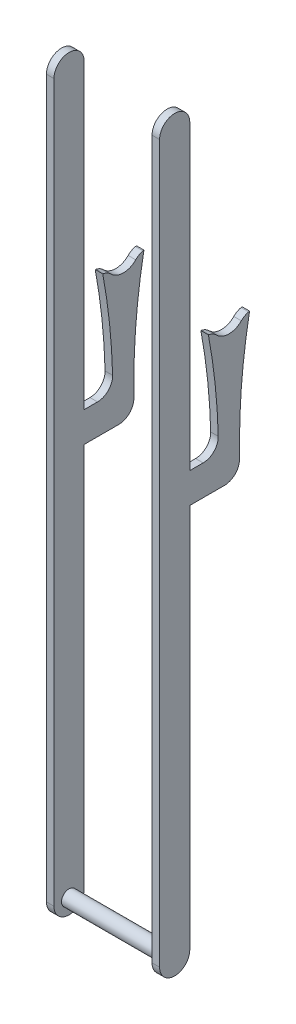
SolidWorks part; units mm, degrees
ref_plane "前视基准面" through (0, 0, 0) normal (0, 0, 1) x (1, 0, 0)
ref_plane "上视基准面" through (0, 0, 0) normal (0, 1, 0) x (1, 0, 0)
ref_plane "右视基准面" through (0, 0, 0) normal (1, 0, 0) x (0, 0, -1)
sketch "草图1" plane through (0, 0, 0) normal (0, 1, 0) x (1, 0, 0)
  line L0 (0, 0) -> (25601.3768, 0) construction
  line L1 (0, 0) -> (0, -25601.3768) construction
  line L2 (-65, -20) -> (-75, -20)
  line L3 (65, 20) -> (75, 20)
  line L4 (65, 20) -> (65, -20)
  line L5 (65, -20) -> (75, -20)
  line L6 (75, 20) -> (75, -20)
  line L7 (65, 20) -> (75, -20) construction
  line L8 (65, -20) -> (75, 20) construction
  line L9 (-75, 20) -> (-75, -20)
  line L10 (-65, 20) -> (-75, 20)
  line L11 (-65, 20) -> (-65, -20)
  point P5 (70, 0)
  dimension "D1" = 10
  dimension "D2" = 40
  dimension "D3" = 130
extrude "凸台-拉伸1" add sketch "草图1" along normal blind 950
sketch "草图2" plane through (75, 0, 0) normal (1, 0, 0) x (0, 0, -1)
  line L0 (-20, 0) -> (20, 0) construction
  circle A0 centre (0, 0) radius 10
  dimension "D1" = 20
extrude "凸台-拉伸2" add sketch "草图2" against normal blind 150
sketch "草图3" plane through (75, 0, 0) normal (1, 0, 0) x (0, 0, -1)
  line L0 (-20, 950) -> (20, 950) construction
  circle A0 centre (0, 950) radius 20
  circle A1 centre (0, 0) radius 20
extrude "凸台-拉伸3" add sketch "草图3" against normal blind 10
sketch "草图4" plane through (-75, 0, 0) normal (-1, 0, 0) x (0, 0, 1)
  line L0 (-20, 950) -> (20, 950) construction
  circle A0 centre (0, 950) radius 20
  circle A1 centre (0, 0) radius 20
extrude "凸台-拉伸4" add sketch "草图4" against normal blind 10
sketch "草图5" plane through (-75, 0, 0) normal (-1, 0, 0) x (0, 0, 1)
  line L0 (-1.9617, 550) -> (-58.0003, 550)
  line L1 (-71.9617, 550) -> (-71.9617, 710) construction
  line L2 (-85.9231, 550) -> (-85.9231, 510)
  line L3 (-85.9231, 510) -> (-1.9617, 510)
  line L4 (-1.9617, 510) -> (-1.9617, 550)
  line L5 (-99.2579, 693.5156) -> (-91.4051, 691.6558)
  line L6 (-52.5183, 691.6558) -> (-44.6655, 693.5156)
  arc A1 (-91.4051, 691.6558) -> (-52.5183, 691.6558) centre (-71.9617, 703.9414) ccw
  arc A2 (-85.9231, 550) -> (-99.2579, 693.5156) centre (-864.8806, 550) ccw
  arc A3 (-58.0003, 550) -> (-44.6655, 693.5156) centre (720.9571, 550) cw
  point P4 (0, 950)
  dimension "D4" = 40
  dimension "D1" = 70
  dimension "D2" = 400
  dimension "D3" = 160
extrude "凸台-拉伸5" add sketch "草图5" against normal blind 10 contours A2 L5 A1 L6 A3 L0 L4 L3 L2
sketch "草图6" plane through (65, 0, 0) normal (-1, 0, 0) x (0, 0, 1)
  line L0 (-1.9617, 550) -> (-58.0003, 550)
  line L1 (-71.9617, 550) -> (-71.9617, 710) construction
  line L2 (-85.9231, 550) -> (-85.9231, 510)
  line L3 (-85.9231, 510) -> (-1.9617, 510)
  line L4 (-1.9617, 510) -> (-1.9617, 550)
  line L5 (-99.2579, 693.5156) -> (-91.4051, 691.6558)
  line L6 (-52.5183, 691.6558) -> (-44.6655, 693.5156)
  arc A0 (-91.4051, 691.6558) -> (-52.5183, 691.6558) centre (-71.9617, 703.9414) ccw
  arc A1 (-85.9231, 550) -> (-99.2579, 693.5156) centre (-864.8806, 550) ccw
  arc A2 (-58.0003, 550) -> (-44.6655, 693.5156) centre (720.9571, 550) cw
  dimension "D5" = 22.9996
  dimension "D6" = 778.9575
  dimension "D1" = 70
  dimension "D2" = 160
  dimension "D3" = 40
  dimension "D4" = 56.0386
  dimension "D7" = 54.5924
  dimension "D8" = 38.8868
  dimension "D9" = 8.0701
  dimension "D10" = 183.5156
extrude "凸台-拉伸6" add sketch "草图6" against normal blind 10
fillet "圆角1" radius 20 8 edges at (70, 691.6558, -91.4051) (70, 691.6558, -52.5183) (-70, 691.6558, -91.4051) (-70, 691.6558, -52.5183) (-70, 510, -85.9231) (-70, 550, -58.0003) (70, 510, -85.9231) (70, 550, -58.0003)
